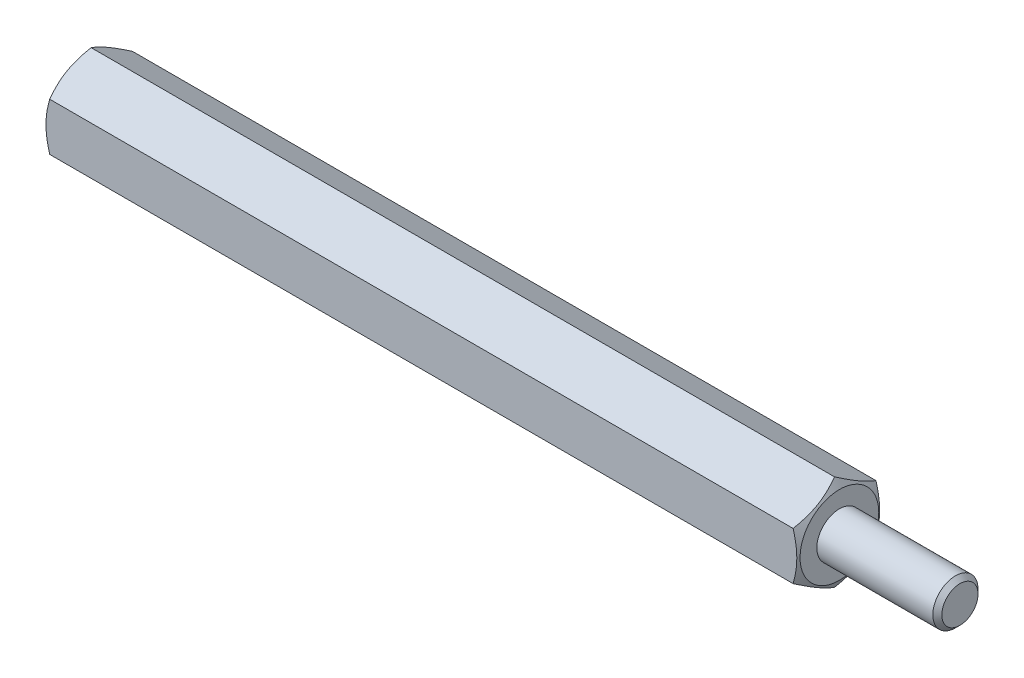
SolidWorks part; units mm, degrees
material "Brass"
ref_plane "Front Plane" through (0, 0, 0) normal (0, 0, 1) x (1, 0, 0)
ref_plane "Top Plane" through (0, 0, 0) normal (0, 1, 0) x (1, 0, 0)
ref_plane "Right Plane" through (0, 0, 0) normal (1, 0, 0) x (0, 0, -1)
sketch "Sketch1" plane through (0, 0, 0) normal (1, 0, 0) x (0, 0, -1)
  line L1 (0, 3.1754) -> (-2.75, 1.5877)
  line L2 (-2.75, 1.5877) -> (-2.75, -1.5877)
  line L3 (-2.75, -1.5877) -> (0, -3.1754)
  line L4 (0, -3.1754) -> (2.75, -1.5877)
  line L5 (2.75, -1.5877) -> (2.75, 1.5877)
  line L6 (2.75, 1.5877) -> (0, 3.1754)
  circle A0 centre (0, 0) radius 2.75 construction
extrude "Boss-Extrude1" add sketch "Sketch1" along normal blind 50
sketch "Sketch2" plane through (50, 0, 0) normal (1, 0, 0) x (0, 0, -1)
  circle A0 centre (0, 0) radius 1.5
extrude "Boss-Extrude2" add sketch "Sketch2" along normal blind 8
sketch "Sketch3" plane through (0, 0, 0) normal (-1, 0, 0) x (0, 0, 1)
  circle A0 centre (0, 0) radius 1.5
extrude "Cut-Extrude1" cut sketch "Sketch3" against normal blind 10
sketch "Sketch4" plane through (0, 0, 0) normal (0, 1, 0) x (1, 0, 0)
  line L0 (0, 0) -> (0, 2.6125)
  line L1 (0, 2.6125) -> (4.3921, 10.2198)
  line L2 (0, 2.6125) -> (0, 10.2198)
  line L3 (0, 10.2198) -> (4.3921, 10.2198)
  line L4 (0, 0) -> (-8.2035, 0) construction
  line L5 (50, 0) -> (50, 2.6125)
  line L6 (50, 2.6125) -> (45.6079, 10.2198)
  line L7 (50, 2.6125) -> (50, 10.2198)
  line L8 (50, 10.2198) -> (45.6079, 10.2198)
  line L9 (0, 0) -> (50, 0)
revolve "Cut-Revolve1" cut sketch "Sketch4" angle 360 about L4
chamfer "Chamfer1" distance 0.3 angle 45 1 edges at (58, 0, -1.5)
